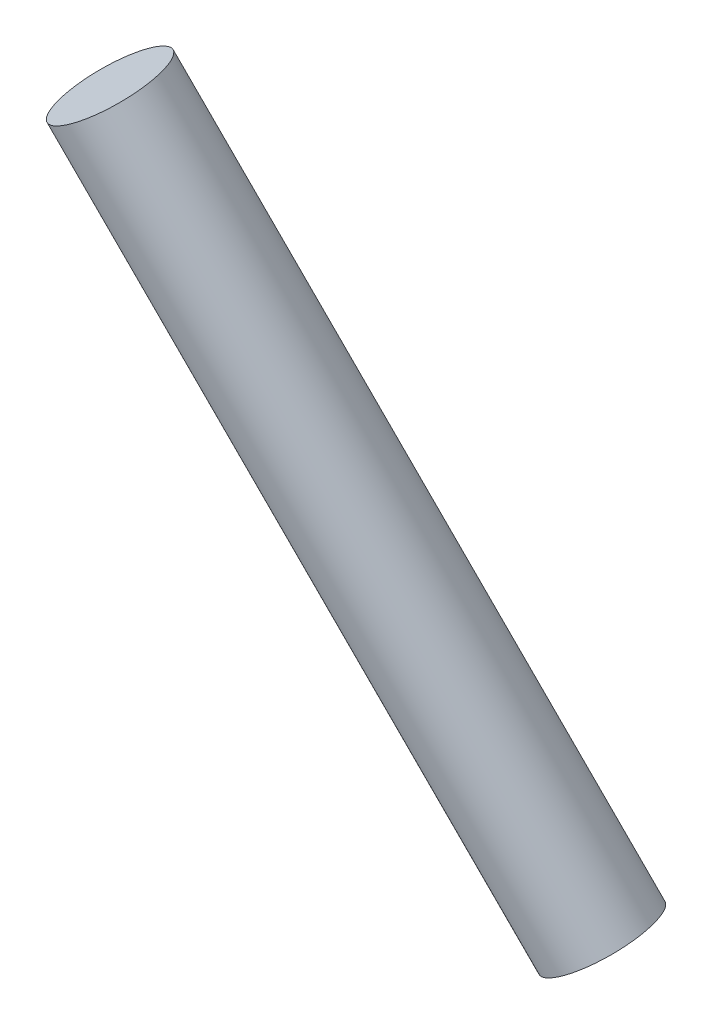
SolidWorks part; units mm, degrees
ref_plane "前视基准面" through (0, 0, 0) normal (0, 0, 1) x (1, 0, 0)
ref_plane "上视基准面" through (0, 0, 0) normal (0, 1, 0) x (1, 0, 0)
ref_plane "右视基准面" through (0, 0, 0) normal (1, 0, 0) x (0, 0, -1)
sketch "草图4" plane through (-17.4073, 27.3806, 4.9883) normal (0.5303, -0.8341, -0.152) x (0.8478, 0.5217, 0.095)
  circle A1 centre (0, 0) radius 2.5
extrude "凸台-拉伸2" add sketch "草图4" against normal blind 35 separate body
